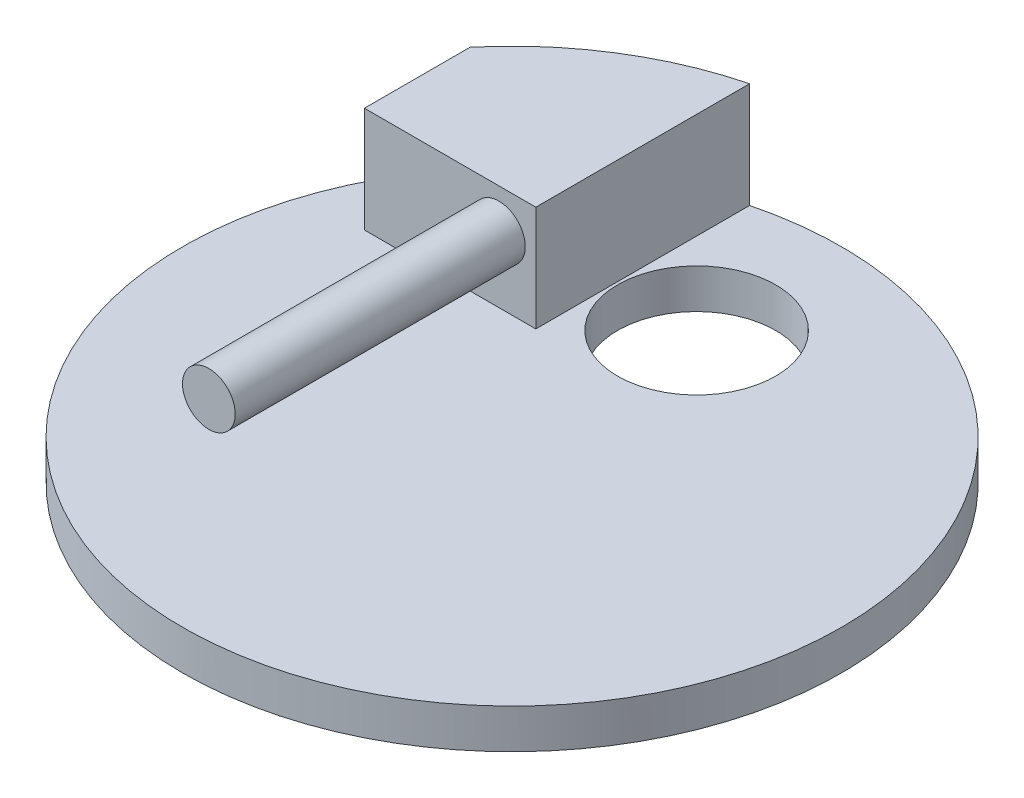
SolidWorks part; units mm, degrees
ref_plane "Front Plane" through (0, 0, 0) normal (0, 0, 1) x (1, 0, 0)
ref_plane "Top Plane" through (0, 0, 0) normal (0, 1, 0) x (1, 0, 0)
ref_plane "Right Plane" through (0, 0, 0) normal (1, 0, 0) x (0, 0, -1)
sketch "Sketch1" plane through (0, 0, 0) normal (0, 1, 0) x (1, 0, 0)
  line L0 (0, 0) -> (0, 12.5) construction
  circle A0 centre (0, 0) radius 12.5
  circle A2 centre (0, 7) radius 3
  dimension "D1" = 25
  dimension "D2" = 6
  dimension "D3" = 7
extrude "Boss-Extrude1" add sketch "Sketch1" along normal blind 1.5
ref_plane "Plane1" through (0, 0, -4) normal (0, 0, 1) x (1, 0, 0)
sketch "Sketch3" plane through (0, 0, -4) normal (0, 0, 1) x (1, 0, 0)
  line L0 (12.5, 1.5) -> (-12.5, 1.5) construction
  circle A0 centre (-4.5, 4) radius 1
  dimension "D3" = 2
  dimension "D1" = 2.5
  dimension "D2" = 4.5
extrude "Boss-Extrude3" add sketch "Sketch3" along normal blind 11 separate body contours A0
sketch "Sketch5" plane through (0, 0, -4) normal (0, 0, 1) x (1, 0, 0)
  line L0 (12.5, 1.5) -> (-12.5, 1.5) construction
  line L1 (-9.6, 1.5) -> (-3.1, 1.5)
  line L2 (-9.6, 1.5) -> (-9.6, 5.5)
  line L3 (-9.6, 5.5) -> (-3.1, 5.5)
  line L4 (-3.1, 1.5) -> (-3.1, 5.5)
  dimension "D1" = 6.5
  dimension "D2" = 4
  dimension "D3" = 3.1
extrude "Boss-Extrude4" add sketch "Sketch5" against normal up to surface (4.0056 mm away)
